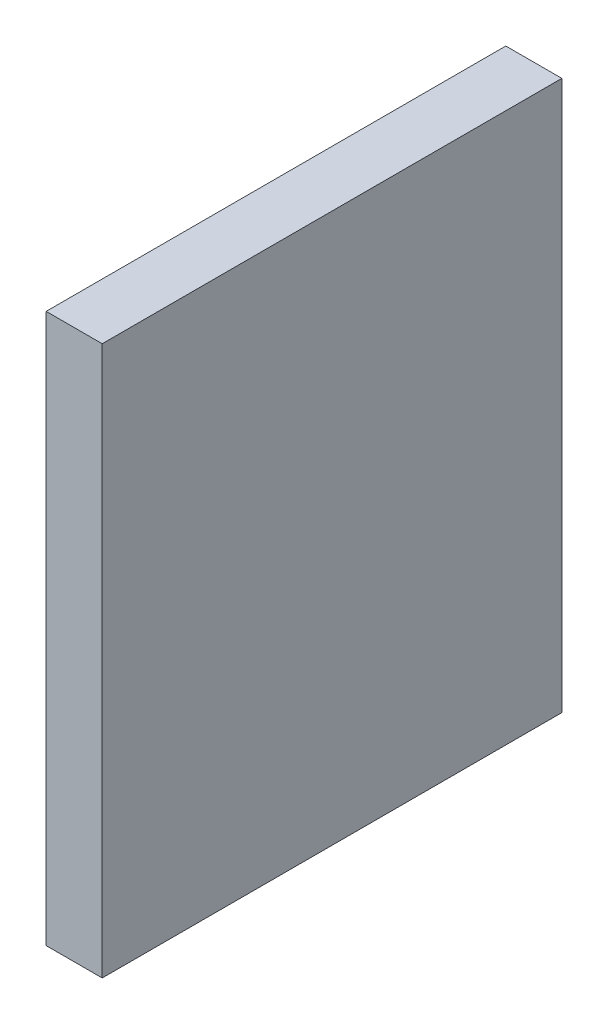
SolidWorks part; units mm, degrees
material "Balsa"
ref_plane "Plano frontal" through (0, 0, 0) normal (0, 0, 1) x (1, 0, 0)
ref_plane "Plano superior" through (0, 0, 0) normal (0, 1, 0) x (1, 0, 0)
ref_plane "Plano direito" through (0, 0, 0) normal (1, 0, 0) x (0, 0, -1)
sketch "Esboço1" plane through (0, 0, 0) normal (1, 0, 0) x (0, 0, -1)
  line L1 (0, 0) -> (-20.5, 0)
  line L2 (0, 0) -> (0, 24.5)
  line L3 (0, 24.5) -> (-20.5, 24.5)
  line L4 (-20.5, 0) -> (-20.5, 24.5)
  dimension "D1" = 20.5
  dimension "D2" = 24.5
extrude "Ressalto-extrusão1" add sketch "Esboço1" along normal blind 2.5
